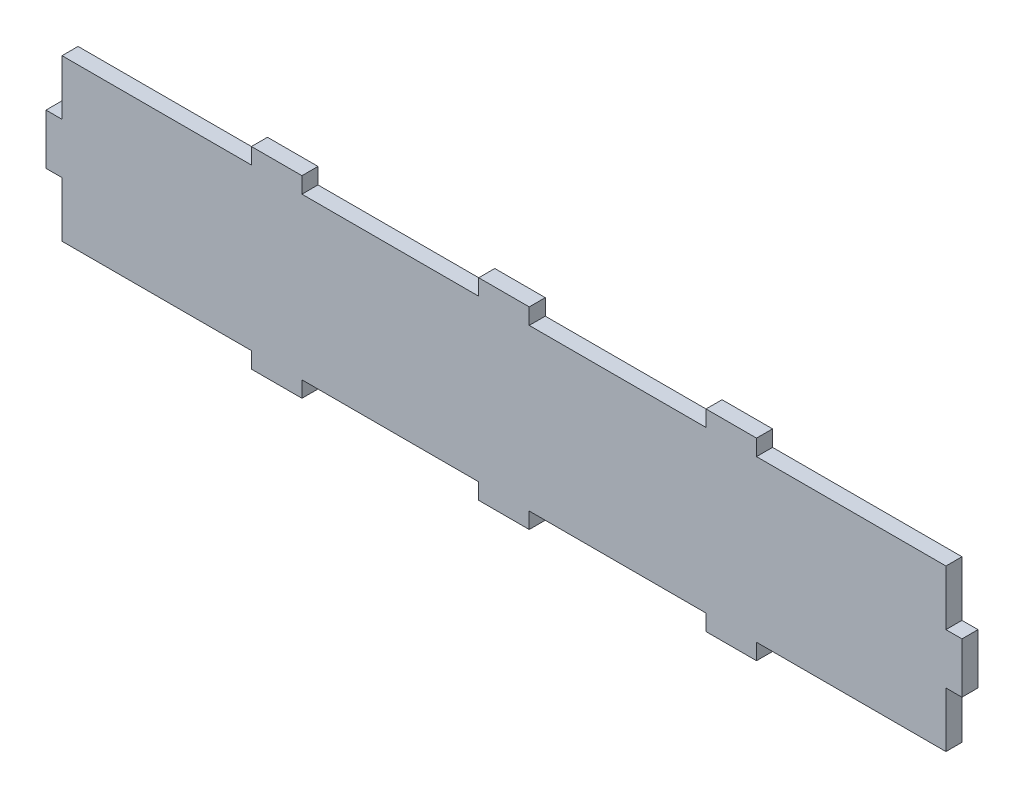
SolidWorks part; units mm, degrees
ref_plane "Alzado" through (0, 0, 0) normal (0, 0, 1) x (1, 0, 0)
ref_plane "Planta" through (0, 0, 0) normal (0, 1, 0) x (1, 0, 0)
ref_plane "Vista lateral" through (0, 0, 0) normal (1, 0, 0) x (0, 0, -1)
sketch "Croquis1" plane through (0, 0, 0) normal (0, 0, 1) x (-1, 0, 0)
  line L1 (-193.65, -6.35) -> (156.35, -6.35)
  line L2 (-193.65, -6.35) -> (-193.65, -70)
  line L3 (-193.65, -70) -> (156.35, -70)
  line L4 (156.35, -6.35) -> (156.35, -70)
  dimension "D1" = 63.65
  dimension "D2" = 350
extrude "Saliente-Extruir1" add sketch "Croquis1" along normal blind 6.35
sketch "Croquis2" plane through (-156.35, 0, 0) normal (-1, 0, 0) x (0, 0, 1)
  line L0 (0, 70) -> (0, 6.35) construction
  line L1 (0, 48.175) -> (6.35, 48.175)
  line L2 (0, 48.175) -> (0, 28.175)
  line L3 (0, 28.175) -> (6.35, 28.175)
  line L4 (6.35, 48.175) -> (6.35, 28.175)
  line L5 (6.35, 70) -> (6.35, 6.35) construction
  point P8 (6.35, 38.175)
  point P9 (6.35, 38.175)
  dimension "D1" = 20
extrude "Saliente-Extruir2" add sketch "Croquis2" along normal blind 6.35
ref_plane "Plano1" through (18.65, 0, 0) normal (1, 0, 0) x (0, 0, -1)
mirror "Simetría1" about plane through (18.65, 0, 0) normal (1, 0, 0) of "Saliente-Extruir2"
sketch "Croquis3" plane through (0, 70, 0) normal (0, 1, 0) x (1, 0, 0)
  line L0 (193.65, 0) -> (-156.35, 0) construction
  line L1 (28.65, 0) -> (8.65, 0)
  line L2 (28.65, 0) -> (28.65, -6.35)
  line L3 (28.65, -6.35) -> (8.65, -6.35)
  line L4 (8.65, 0) -> (8.65, -6.35)
  line L5 (193.65, -6.35) -> (-156.35, -6.35) construction
  line L14 (118.65, 0) -> (98.65, 0)
  line L15 (118.65, 0) -> (118.65, -6.35)
  line L16 (118.65, -6.35) -> (98.65, -6.35)
  line L17 (98.65, 0) -> (98.65, -6.35)
  line L18 (-61.35, 0) -> (-81.35, 0)
  line L19 (-61.35, 0) -> (-61.35, -6.35)
  line L20 (-61.35, -6.35) -> (-81.35, -6.35)
  line L21 (-81.35, 0) -> (-81.35, -6.35)
  point P8 (18.65, 0)
  point P9 (18.65, 0)
  dimension "D1" = 20
extrude "Saliente-Extruir3" add sketch "Croquis3" along normal blind 6.35
ref_plane "Plano2" through (0, 38.175, 0) normal (0, 1, 0) x (1, 0, 0)
mirror "Simetría2" about plane through (0, 38.175, 0) normal (0, 1, 0) of "Saliente-Extruir3"
